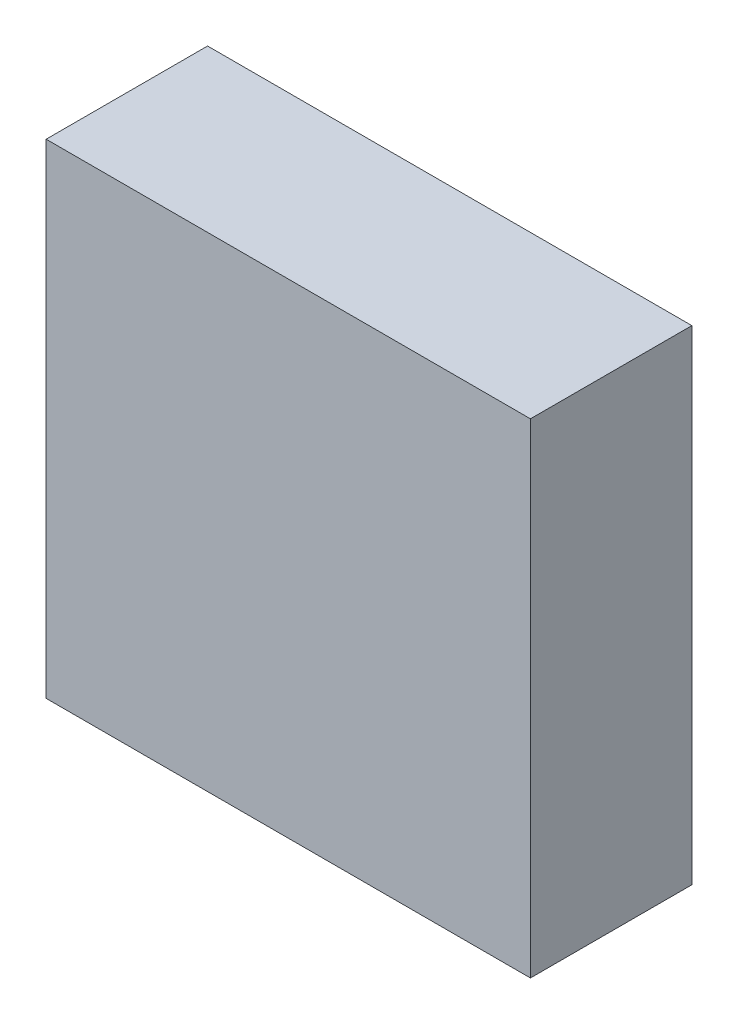
SolidWorks part; units mm, degrees
ref_plane "前视基准面" through (0, 0, 0) normal (0, 0, 1) x (1, 0, 0)
ref_plane "上视基准面" through (0, 0, 0) normal (0, 1, 0) x (1, 0, 0)
ref_plane "右视基准面" through (0, 0, 0) normal (1, 0, 0) x (0, 0, -1)
sketch "草图1" plane through (0, 0, 0) normal (0, 0, 1) x (1, 0, 0)
  line L1 (-31.2159, 27.9231) -> (-1.2159, 27.9231)
  line L2 (-31.2159, 27.9231) -> (-31.2159, -2.0769)
  line L3 (-31.2159, -2.0769) -> (-1.2159, -2.0769)
  line L4 (-1.2159, 27.9231) -> (-1.2159, -2.0769)
  dimension "D1" = 30
  dimension "D2" = 30
extrude "凸台-拉伸1" add sketch "草图1" along normal blind 10
